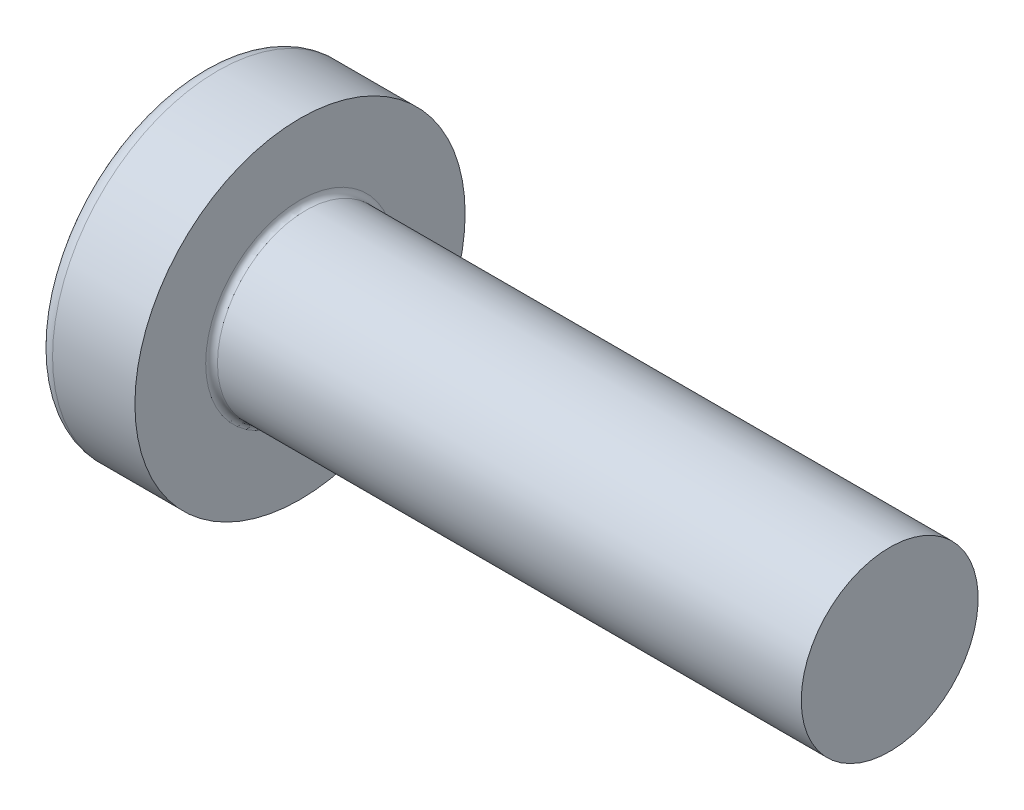
SolidWorks part; units mm, degrees
ref_plane "Plane1" through (0, 0, 0) normal (0, 0, 1) x (1, 0, 0)
ref_plane "Plane2" through (0, 0, 0) normal (0, 1, 0) x (1, 0, 0)
ref_plane "Plane3" through (0, 0, 0) normal (1, 0, 0) x (0, 0, -1)
sketch "BodySke" plane through (0, 0, 0) normal (0, 0, 1) x (1, 0, 0)
  line L0 (2.4, 1.5) -> (2.4, 2.8)
  line L1 (2.65, 6.35) -> (2.65, -3.175) construction
  line L2 (-25.4, 0) -> (127, 0) construction
  line L3 (12.4, 0) -> (0, 0)
  line L4 (2.4, 1.5) -> (12.4, 1.5)
  line L5 (12.4, 1.5) -> (12.4, 0)
  line L6 (1.0035, 2.8) -> (2.4, 2.8)
  line L8 (2.4, 6.35) -> (2.4, -3.175) construction
  arc A0 (0.7754, 2.6744) -> (0, 0) centre (5, 0) ccw
  arc A2 (0.7754, 2.6744) -> (1.0035, 2.8) centre (1.0035, 2.53) cw
revolve "Base-Revolve" add sketch "BodySke"
cosmetic thread "ThreadCosmetic" [suppressed]
fillet "Fillet1" radius 0.1 1 edges at (2.4, 0, 1.5)
sketch "Sketch3" plane through (0, 0, 0) normal (1, 0, 0) x (0, 0, -1)
  line L0 (0.37, -1.4) -> (-0.37, -1.4)
  line L1 (0.37, -1.4) -> (0.37, 1.4)
  line L2 (-0.37, 1.4) -> (0.37, 1.4)
  line L3 (-0.37, 1.4) -> (-0.37, -1.4)
ref_plane "Plane4" through (1.75, 0, 0) normal (1, 0, 0) x (0, 0, -1)
sketch "Sketch4" plane through (1.75, 0, 0) normal (1, 0, 0) x (0, 0, -1)
  line L0 (0.37, -0.5275) -> (-0.37, -0.5275)
  line L1 (0.37, -0.5275) -> (0.37, 0.5275)
  line L2 (-0.37, 0.5275) -> (0.37, 0.5275)
  line L3 (-0.37, 0.5275) -> (-0.37, -0.5275)
loft "Recess" cut profiles "Sketch3", "Sketch4"
pattern_circular "RecPat" count 2 every 90 about axis through (0, 0, 0) along (1, 0, 0) of "Recess"
sketch "RecCorSke" plane through (0, 0, 0) normal (0, 0, 1) x (1, 0, 0)
  line L0 (-3.175, 0) -> (15.875, 0) construction
  line L1 (-25.4, 0) -> (127, 0) construction
  line L2 (0, 0) -> (0, 0.6784)
  line L3 (0, 0.6784) -> (1.75, 0.556)
  line L4 (1.75, 0.556) -> (1.9307, 0)
  line L5 (1.9307, 0) -> (0, 0)
  dimension "Draft_angle" = 4
  dimension "Bottom_angle" = 18
revolve "RecessCore" cut sketch "RecCorSke" angle 360 about L0
sketch "ThdSchSke" plane through (0, 0, 0) normal (0, 0, 1) x (1, 0, 0)
  line L0 (3.4, -1.2195) -> (3.2036, -1.5)
  line L1 (3.4, -1.2195) -> (3.5964, -1.5)
  line L2 (3.5964, -1.5) -> (3.5964, -1.875)
  line L3 (-3.175, 0) -> (5.1513, 0) construction
  line L5 (3.5964, -1.875) -> (3.2036, -1.875)
  line L6 (3.2036, -1.875) -> (3.2036, -1.5)
  dimension "SideAngle" = 55
  dimension "VeeAngle" = 70
revolve "ThreadSchematic" [suppressed] cut sketch "ThdSchSke" angle 360 about L3
pattern_linear "ThdSchPat" [suppressed]
equation "\"D1@Sketch3\" = \"Cross_dia@Sketch3\" / 2"
equation "\"D2@Sketch3\" = \"Cross_width@Sketch3\" / 2"
equation "\"Depth@RecCorSke\" = \"Cross_depth@Plane4\""
equation "\"D1@Sketch4\" = \"Cross_width@Sketch3\""
equation "\"D2@Sketch4\" = \"Cross_dia@Sketch3\" - 2.0 * \"Cross_depth@Plane4\" * tan(26.5  * 0.017453292)"
equation "\"D3@Sketch4\" = \"D1@Sketch4\" / 2"
equation "\"D4@Sketch4\" = \"D2@Sketch4\" / 2"
equation "\"Thread_length@ThreadCosmetic\" = ((sgn( (\"Length@BodySke\" - \"Advance@BodySke\" * 2.0 ) - \"Thread_nom@BodySke\" )-1)*( (\"Length@BodySke\" - \"Advance@BodySke\" * 2.0 ) - \"Thread_nom@BodySke\" ))/-2+ \"Thread_nom@BodySke\""
equation "\"Thread_minor@ThdSchSke\" = \"Thread_minor@ThreadCosmetic\""
equation "\"Diameter@ThdSchSke\" = \"Diameter@BodySke\""
equation "\"Overcut@ThdSchSke\" = \"Diameter@BodySke\" * 1.25"
equation "\"Start@ThdSchSke\" = \"Head_ht@BodySke\" + \"Length@BodySke\" - \"Thread_length@ThreadCosmetic\"  '---Non-countersunk---"
equation "\"Num_threads@ThdSchPat\" = int( \"Thread_length@ThreadCosmetic\" / \"Advance@BodySke\" + 0.999 )  + 1"
equation "\"Advance@ThdSchPat\" = \"Thread_length@ThreadCosmetic\" /  (\"Num_threads@ThdSchPat\" - 1) 'relax it"
